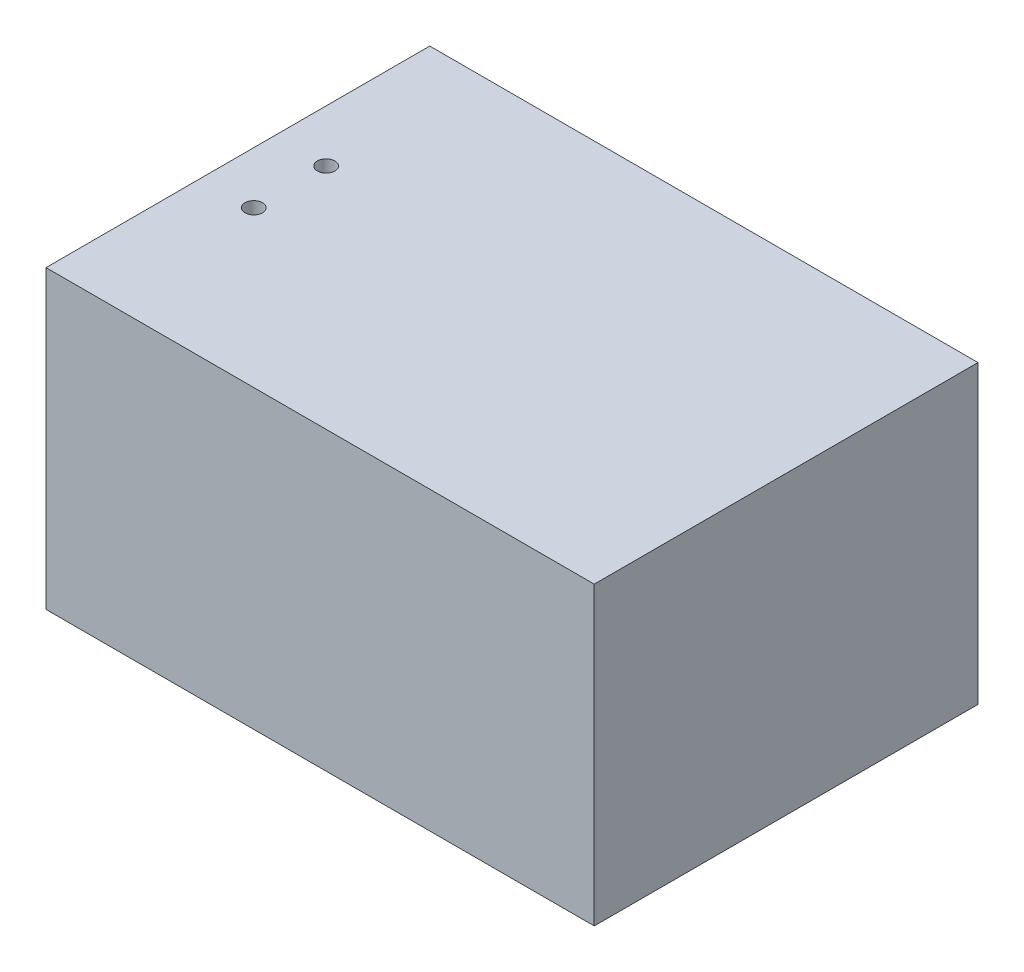
SolidWorks part; units mm, degrees
ref_plane "Ebene vorne" through (0, 0, 0) normal (0, 0, 1) x (1, 0, 0)
ref_plane "Ebene oben" through (0, 0, 0) normal (0, 1, 0) x (1, 0, 0)
ref_plane "Ebene rechts" through (0, 0, 0) normal (1, 0, 0) x (0, 0, -1)
sketch "Skizze1" plane through (0, 0, 0) normal (0, -1, 0) x (1, 0, 0)
  line L0 (-50, 35) -> (50, -35) construction
  line L1 (-50, -35) -> (50, -35)
  line L2 (-50, -35) -> (-50, 35)
  line L3 (-50, 35) -> (50, 35)
  line L4 (50, -35) -> (50, 35)
  line L5 (50, 35) -> (-50, -35) construction
  line L6 (0, 47.2006) -> (0, -66.4682) construction
  line L11 (76.0628, 0) -> (-97.0729, 0) construction
  point P0 (0, 0)
  point P6 (0, 0)
  dimension "D1" = 100
  dimension "D2" = 70
extrude "Aufsatz-Linear austragen1" add sketch "Skizze1" along normal blind 4
sketch "Skizze2" plane through (0, -4, 0) normal (0, -1, 0) x (1, 0, 0)
  line L0 (-50, 35) -> (-50, -35) construction
  line L1 (-50, -35) -> (50, -35) construction
  line L2 (50, -35) -> (50, 35) construction
  line L3 (50, 35) -> (-50, 35) construction
  line L4 (-50, 35) -> (-50, -35)
  line L5 (-50, -35) -> (50, -35)
  line L6 (50, -35) -> (50, 35)
  line L7 (50, 35) -> (-50, 35)
  line L8 (0, 48.2959) -> (0, -41.3019) construction
  line L9 (-97.8299, 0) -> (88.0132, 0) construction
  line L10 (-48, 24.9) -> (-48, -24.9)
  line L11 (-39.9, -33) -> (39.9, -33)
  line L12 (48, -24.9) -> (48, 24.9)
  line L14 (-48, -33) -> (48, -33) construction
  line L15 (48, -33) -> (48, 33) construction
  line L16 (-48, 33) -> (-48, -33) construction
  line L17 (48, 33) -> (-48, 33) construction
  line L18 (39.9, 33) -> (-39.9, 33)
  line L19 (-45, 24.9) -> (-48, 24.9)
  line L20 (-39.9, 30) -> (-39.9, 33)
  line L21 (39.9, 30) -> (39.9, 33)
  line L22 (45, 24.9) -> (48, 24.9)
  line L23 (45, -24.9) -> (48, -24.9)
  line L24 (39.9, -30) -> (39.9, -33)
  line L25 (-39.9, -30) -> (-39.9, -33)
  line L26 (-45, -24.9) -> (-48, -24.9)
  arc A0 (-45, 24.9) -> (-39.9, 30) centre (-45, 30) ccw
  circle A1 centre (-45, 30) radius 2.1
  circle A2 centre (45, 30) radius 2.1
  arc A3 (45, 24.9) -> (39.9, 30) centre (45, 30) cw
  arc A4 (45, -24.9) -> (39.9, -30) centre (45, -30) ccw
  circle A5 centre (45, -30) radius 2.1
  circle A6 centre (-45, -30) radius 2.1
  arc A7 (-45, -24.9) -> (-39.9, -30) centre (-45, -30) cw
  circle A8 centre (-45, 30) radius 5.1 construction
  dimension "D2" = 4.2
  dimension "D4" = 2
  dimension "D5" = 5
  dimension "D6" = 5
  dimension "D1" = 3
  dimension "D3" = 2
extrude "Aufsatz-Linear austragen2" add sketch "Skizze2" along normal blind 50
sketch "Skizze3" plane through (0, -54, 0) normal (0, -1, 0) x (1, 0, 0)
  line L0 (0, 39.2352) -> (0, -39.2552) construction
  line L1 (-65.7274, 0) -> (73.0484, 0) construction
  circle A1 centre (-45, 30) radius 2.8
  circle A2 centre (45, 30) radius 2.8
  circle A4 centre (45, -30) radius 2.8
  circle A5 centre (-45, -30) radius 2.8
  dimension "D1" = 5.6
extrude "Schnitt-Linear austragen1" cut sketch "Skizze3" against normal blind 9
sketch "Skizze4" plane through (0, -4, 0) normal (0, -1, 0) x (1, 0, 0)
  line L0 (48, -24.9) -> (48, 24.9) construction
  line L1 (-22, 20) -> (38, 20)
  line L2 (-22, 20) -> (-22, -20)
  line L3 (-22, -20) -> (38, -20)
  line L4 (38, 20) -> (38, -20)
  line L5 (-22, 20) -> (38, -20) construction
  line L6 (-22, -20) -> (38, 20) construction
  line L8 (-72.5772, 0) -> (78.3322, 0) construction
  point P0 (8, 0)
  dimension "D1" = 10
  dimension "D2" = 60
  dimension "D3" = 40
extrude "Schnitt-Linear austragen2" [suppressed] cut sketch "Skizze4" against normal blind 1
sketch "Skizze5" plane through (0, -4, 0) normal (0, -1, 0) x (1, 0, 0)
  line L0 (72.0852, 0) -> (-67.5884, 0) construction
  line L1 (-40.5, 30.3943) -> (-40.5, -43.2403) construction
  line L2 (-48, 24.9) -> (-48, -24.9) construction
  circle A0 centre (-40.5, 6.6) radius 1.6
  circle A1 centre (-40.5, -6.6) radius 1.6
  dimension "D1" = 5
  dimension "D2" = 3.2
  dimension "D3" = 7.5
extrude "Schnitt-Linear austragen3" cut sketch "Skizze5" against normal up to next
sketch "Skizze6" plane through (0, 0, -35) normal (0, 0, -1) x (1, 0, 0)
  line L0 (-69.3424, 30) -> (97.5008, 30) construction
  line L1 (0, -10.4472) -> (0, 101.6661) construction
  line L2 (-50, 0) -> (50, 0) construction
  line L3 (15.0246, 39) -> (35.0246, 39)
  line L4 (15.0246, 39) -> (15.0246, 54)
  line L5 (15.0246, 54) -> (35.0246, 54)
  line L6 (35.0246, 39) -> (35.0246, 54)
  line L7 (15.0246, 39) -> (35.0246, 54) construction
  line L8 (15.0246, 54) -> (35.0246, 39) construction
  line L9 (-50, 54) -> (50, 54) construction
  circle A0 centre (-23.3784, 30) radius 2.1
  circle A1 centre (23.3784, 30) radius 2.1
  point P9 (25.0246, 46.5)
  dimension "D1" = 4.2
  dimension "D2" = 20
  dimension "D3" = 15
  dimension "D4" = 30
extrude "Schnitt-Linear austragen4" cut sketch "Skizze6" against normal up to surface (2 mm away) up to face at (0, -29, -33)
sketch "Skizze7" plane through (0, 0, -33) normal (0, 0, 1) x (1, 0, 0)
  line L0 (-17.6049, -30) -> (-20.4916, -25)
  line L1 (0, 17.1666) -> (0, -68.5391) construction
  line L14 (-19.3369, -30) -> (-21.3576, -26.5)
  line L15 (-21.3576, -26.5) -> (-25.3991, -26.5)
  line L16 (-25.3991, -26.5) -> (-27.4198, -30)
  line L17 (-27.4198, -30) -> (-25.3991, -33.5)
  line L18 (-25.3991, -33.5) -> (-21.3576, -33.5)
  line L19 (-21.3576, -33.5) -> (-19.3369, -30)
  line L20 (-20.4916, -25) -> (-26.2651, -25)
  line L21 (-26.2651, -25) -> (-29.1519, -30)
  line L22 (-29.1519, -30) -> (-26.2651, -35)
  line L23 (-26.2651, -35) -> (-20.4916, -35)
  line L24 (-20.4916, -35) -> (-17.6049, -30)
  line L25 (20.4916, -35) -> (17.6049, -30)
  line L26 (26.2651, -35) -> (20.4916, -35)
  line L27 (29.1519, -30) -> (26.2651, -35)
  line L28 (26.2651, -25) -> (29.1519, -30)
  line L29 (20.4916, -25) -> (26.2651, -25)
  line L31 (21.3576, -33.5) -> (19.3369, -30)
  line L32 (25.3991, -33.5) -> (21.3576, -33.5)
  line L33 (27.4198, -30) -> (25.3991, -33.5)
  line L34 (25.3991, -26.5) -> (27.4198, -30)
  line L35 (21.3576, -26.5) -> (25.3991, -26.5)
  line L36 (19.3369, -30) -> (21.3576, -26.5)
  line L37 (17.6049, -30) -> (20.4916, -25)
  circle A0 centre (-23.3784, -30) radius 3.5 construction
  circle A1 centre (-23.3784, -30) radius 5 construction
  circle A2 centre (23.3784, -30) radius 3.5 construction
  circle A3 centre (23.3784, -30) radius 5 construction
  dimension "D1" = 7
  dimension "D2" = 1.5
extrude "Aufsatz-Linear austragen3" add sketch "Skizze7" along normal blind 5
sketch "Skizze8" [suppressed] plane through (0, 0, 0) normal (0, 1, 0) x (-1, 0, 0)
  line L0 (-38.25, 20.25) -> (-38.25, -20.25)
  line L1 (-38.25, -20.25) -> (22.25, -20.25)
  line L2 (22.25, -20.25) -> (22.25, 20.25)
  line L3 (22.25, 20.25) -> (-38.25, 20.25)
  line L4 (-38, 20) -> (-38, -20)
  line L5 (22, 20) -> (-38, 20)
  line L6 (22, -20) -> (22, 20)
  line L7 (-38, -20) -> (22, -20)
  line L8 (-38, 20) -> (-38, -20)
  line L9 (22, 20) -> (-38, 20)
  line L10 (22, -20) -> (22, 20)
  line L11 (-38, -20) -> (22, -20)
  dimension "D1" = 0
  dimension "D2" = 0.25
extrude "Schnitt-Linear austragen5" [suppressed] cut sketch "Skizze8" against normal blind 0.4
sketch "Skizze9" [suppressed] plane through (0, 0, 0) normal (0, 1, 0) x (-1, 0, 0)
  line L1 (-8, 20) -> (-8, -20) construction
  line L2 (-38, -20) -> (22, -20) construction
  line L3 (22, 20) -> (-38, 20) construction
  text T0 "<b>Karte</b>\r\n<b>hier</b>\r\n<b>auflegen</b>" font "Century Gothic" height 5
extrude "Schnitt-Linear austragen6" [suppressed] cut sketch "Skizze9" against normal blind 0.4
sketch "Sketch1" [suppressed] plane through (0, 0, -27.5) normal (0, 0, -1) x (-1, 0, 0)
  line L0 (29.1216, -44.15) -> (24.1216, -44.15) construction
  line L1 (24.1216, -48.35) -> (29.1216, -48.35) construction
  line L2 (-7.8784, -44.15) -> (-12.8784, -44.15) construction
  line L3 (-12.8784, -48.35) -> (-7.8784, -48.35) construction
  line L4 (29.1216, -44.15) -> (24.1216, -44.15)
  line L5 (24.1216, -48.35) -> (29.1216, -48.35)
  line L6 (-7.8784, -44.15) -> (-12.8784, -44.15)
  line L7 (-12.8784, -48.35) -> (-7.8784, -48.35)
  arc A0 (29.1216, -48.35) -> (29.1216, -44.15) centre (29.1216, -46.25) ccw construction
  arc A1 (24.1216, -44.15) -> (24.1216, -48.35) centre (24.1216, -46.25) ccw construction
  arc A2 (-7.8784, -48.35) -> (-7.8784, -44.15) centre (-7.8784, -46.25) ccw construction
  arc A3 (-12.8784, -44.15) -> (-12.8784, -48.35) centre (-12.8784, -46.25) ccw construction
  arc A4 (29.1216, -48.35) -> (29.1216, -44.15) centre (29.1216, -46.25) ccw
  arc A5 (24.1216, -44.15) -> (24.1216, -48.35) centre (24.1216, -46.25) ccw
  arc A6 (-7.8784, -48.35) -> (-7.8784, -44.15) centre (-7.8784, -46.25) ccw
  arc A7 (-12.8784, -44.15) -> (-12.8784, -48.35) centre (-12.8784, -46.25) ccw
sketch "Sketch2" plane through (0, -4, 0) normal (0, -1, 0) x (1, 0, 0)
  line L0 (-63.6704, 0) -> (65.2321, 0) construction
  line L1 (0, -65.6879) -> (0, 77.9042) construction
  line L2 (-35, -20) -> (-35, 20) construction
  line L3 (-35, 20) -> (25, 20) construction
  line L4 (25, 20) -> (25, -20) construction
  line L5 (25, -20) -> (-35, -20) construction
  circle A0 centre (-28, -12.5) radius 3.95
  circle A1 centre (-28, -12.5) radius 1.45
  circle A2 centre (9, -16.5) radius 3.95
  circle A3 centre (9, -16.5) radius 1.45
  circle A4 centre (9, 16.5) radius 1.45
  circle A5 centre (9, 16.5) radius 3.95
  circle A6 centre (-28, 12.5) radius 1.45
  circle A7 centre (-28, 12.5) radius 3.95
  dimension "D2" = 2.9
  dimension "D9" = 2.5
  dimension "D10" = 2.9
  dimension "D13" = 2.5
  dimension "D3" = 7
  dimension "D4" = 25
  dimension "D5" = 40
  dimension "D6" = 60
  dimension "D7" = 20
  dimension "D8" = 25
  dimension "D11" = 33
  dimension "D12" = 16
extrude "Boss-Extrude1" add sketch "Sketch2" along normal blind 5
